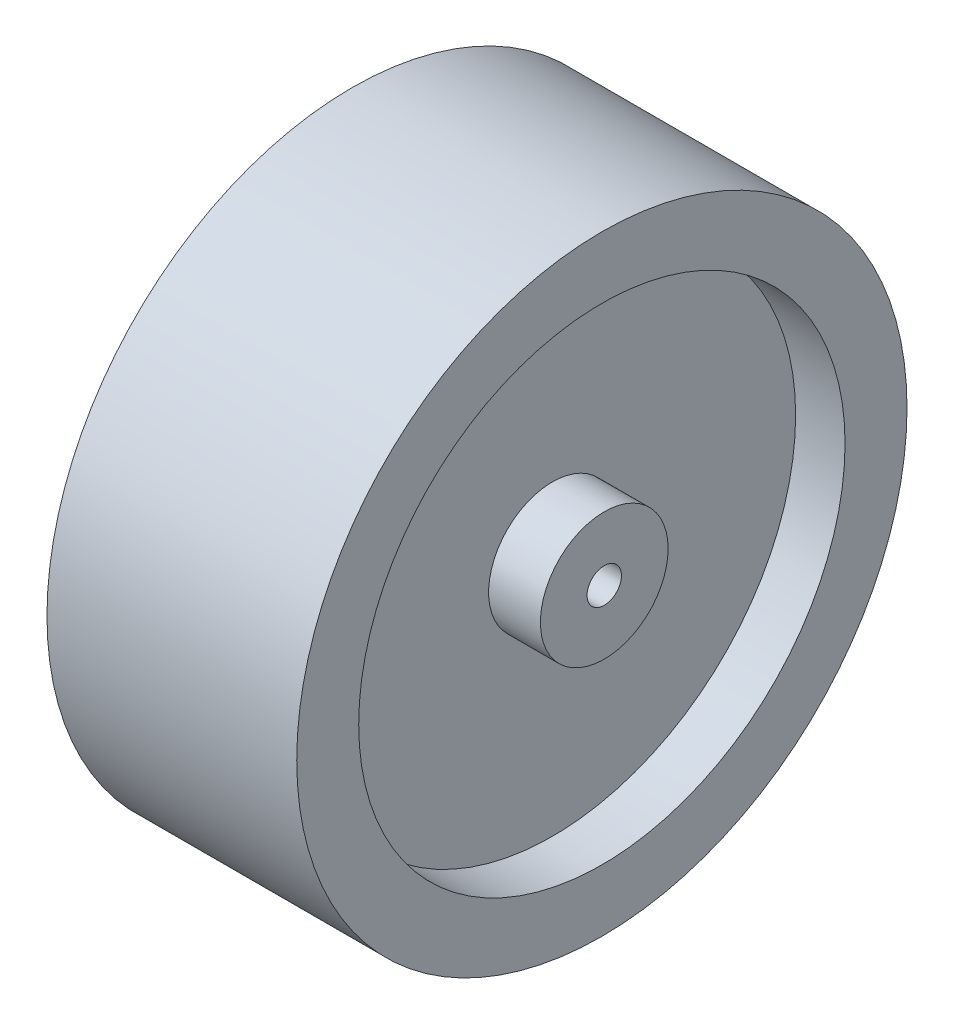
SolidWorks part; units mm, degrees
ref_plane "Front Plane" through (0, 0, 0) normal (0, 0, 1) x (1, 0, 0)
ref_plane "Top Plane" through (0, 0, 0) normal (0, 1, 0) x (1, 0, 0)
ref_plane "Right Plane" through (0, 0, 0) normal (1, 0, 0) x (0, 0, -1)
sketch "Sketch2" plane through (0, 0, 0) normal (1, 0, 0) x (0, 0, -1)
  circle A0 centre (0, 0) radius 32.5
extrude "Boss-Extrude1" add sketch "Sketch2" along normal blind 26.6 contours A0
sketch "Sketch3" plane through (26.6, 0, 0) normal (1, 0, 0) x (0, 0, -1)
  circle A0 centre (0, 0) radius 25.9
extrude "Cut-Extrude2" cut sketch "Sketch3" against normal blind 5.264
sketch "Sketch4" plane through (0, 0, 0) normal (-1, 0, 0) x (0, 0, 1)
  circle A0 centre (0, 0) radius 25.9
extrude "Cut-Extrude3" cut sketch "Sketch4" against normal blind 13.646
sketch "Sketch5" plane through (13.646, 0, 0) normal (-1, 0, 0) x (0, 0, 1)
  circle A0 centre (0, 0) radius 6.8
extrude "Boss-Extrude2" add sketch "Sketch5" along normal blind 13.646
sketch "Sketch6" plane through (21.336, 0, 0) normal (1, 0, 0) x (0, 0, -1)
  circle A0 centre (0, 0) radius 6.8
extrude "Boss-Extrude3" add sketch "Sketch6" along normal blind 5.518
sketch "Sketch7" plane through (26.854, 0, 0) normal (1, 0, 0) x (0, 0, -1)
  circle A0 centre (0, 0) radius 1.83
extrude "Cut-Extrude4" cut sketch "Sketch7" against normal blind 38.03 and the other way blind 28.702
scale "Scale1" scale about centroid uniform scaling yes scale factor 0.8
scale "Scale2" scale about centroid uniform scaling yes scale factor 0.8
scale "Scale3" scale about centroid uniform scaling yes scale factor 0.8
